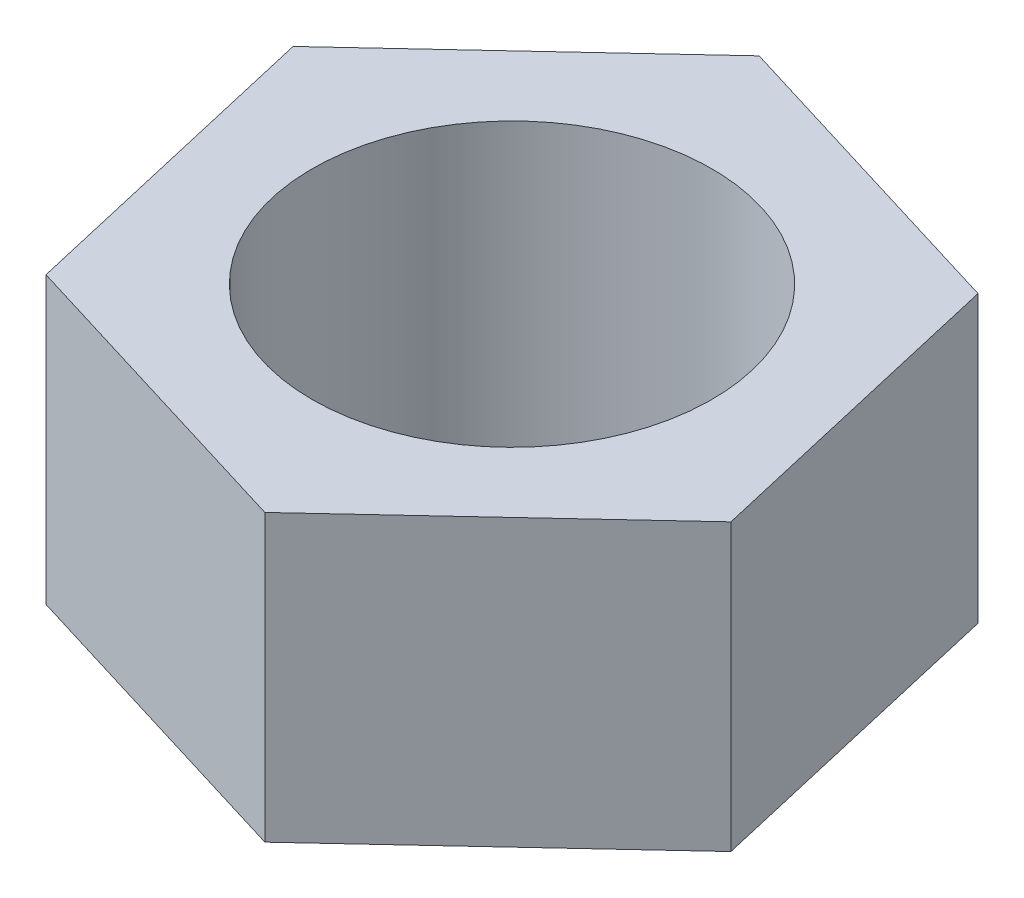
SolidWorks part; units mm, degrees
ref_plane "Спереди" through (0, 0, 0) normal (0, 0, 1) x (1, 0, 0)
ref_plane "Сверху" through (0, 0, 0) normal (0, 1, 0) x (1, 0, 0)
ref_plane "Справа" through (0, 0, 0) normal (1, 0, 0) x (0, 0, -1)
sketch "Эскиз1" plane through (0, 0, 0) normal (0, 1, 0) x (1, 0, 0)
  line L1 (2.5965, -11.2513) -> (11.0421, -3.3771)
  line L2 (11.0421, -3.3771) -> (8.4457, 7.8742)
  line L3 (8.4457, 7.8742) -> (-2.5965, 11.2513)
  line L4 (-2.5965, 11.2513) -> (-11.0421, 3.3771)
  line L5 (-11.0421, 3.3771) -> (-8.4457, -7.8742)
  line L6 (-8.4457, -7.8742) -> (2.5965, -11.2513)
  circle A0 centre (0, 0) radius 10 construction
  circle A1 centre (0, 0) radius 7
extrude "Вытянуть1" add sketch "Эскиз1" along normal blind 10
